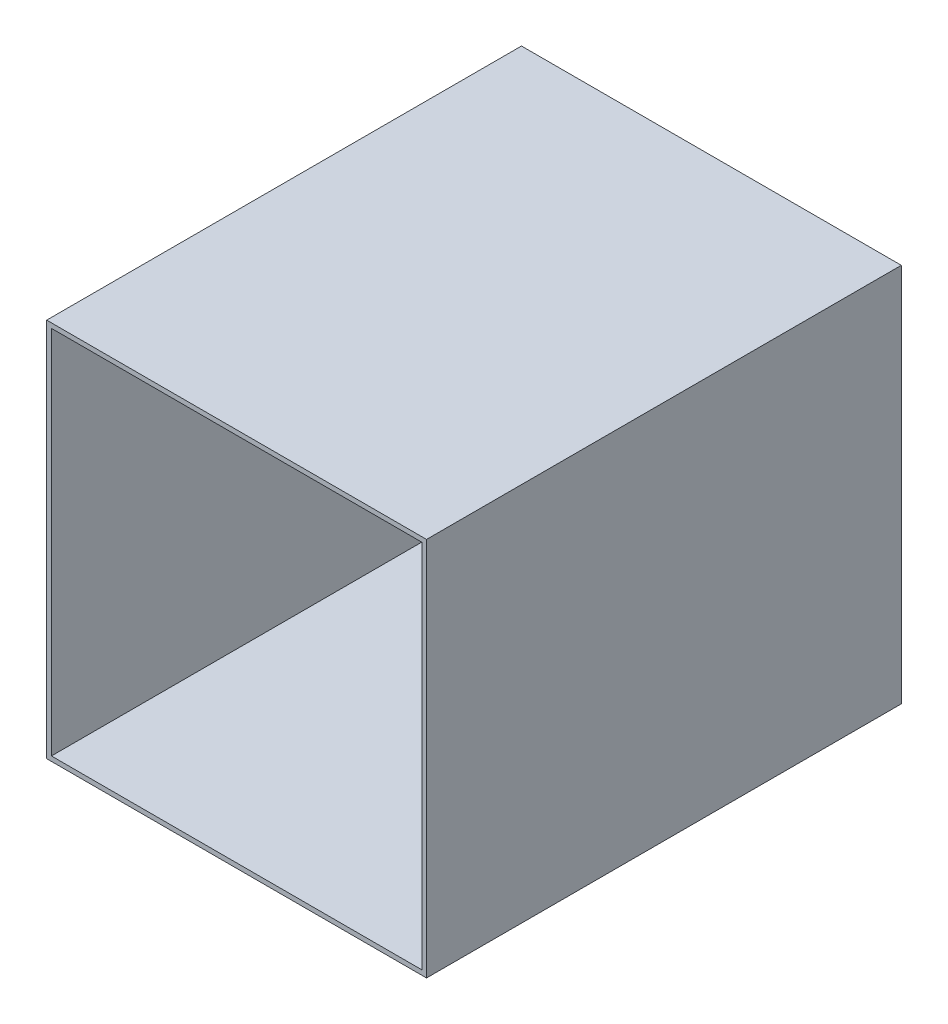
SolidWorks part; units mm, degrees
ref_plane "Front Plane" through (0, 0, 0) normal (0, 0, 1) x (1, 0, 0)
ref_plane "Top Plane" through (0, 0, 0) normal (0, 1, 0) x (1, 0, 0)
ref_plane "Right Plane" through (0, 0, 0) normal (1, 0, 0) x (0, 0, -1)
sketch "Sketch1" plane through (0, 0, 0) normal (0, 0, 1) x (1, 0, 0)
  line L1 (-0.04, -0.04) -> (0.04, -0.04)
  line L2 (-0.04, -0.04) -> (-0.04, 0.04)
  line L3 (-0.04, 0.04) -> (0.04, 0.04)
  line L4 (0.04, -0.04) -> (0.04, 0.04)
  line L5 (-0.04, -0.04) -> (0.04, 0.04) construction
  line L6 (-0.04, 0.04) -> (0.04, -0.04) construction
  point P0 (0, 0)
  dimension "D1" = 0.08
  dimension "D2" = 0.08
extrude "Boss-Extrude1" add sketch "Sketch1" along normal blind 0.1
shell "Shell1" thickness 0.001
equation "\"D2@Sketch1\"=\"D1@Sketch1\""
